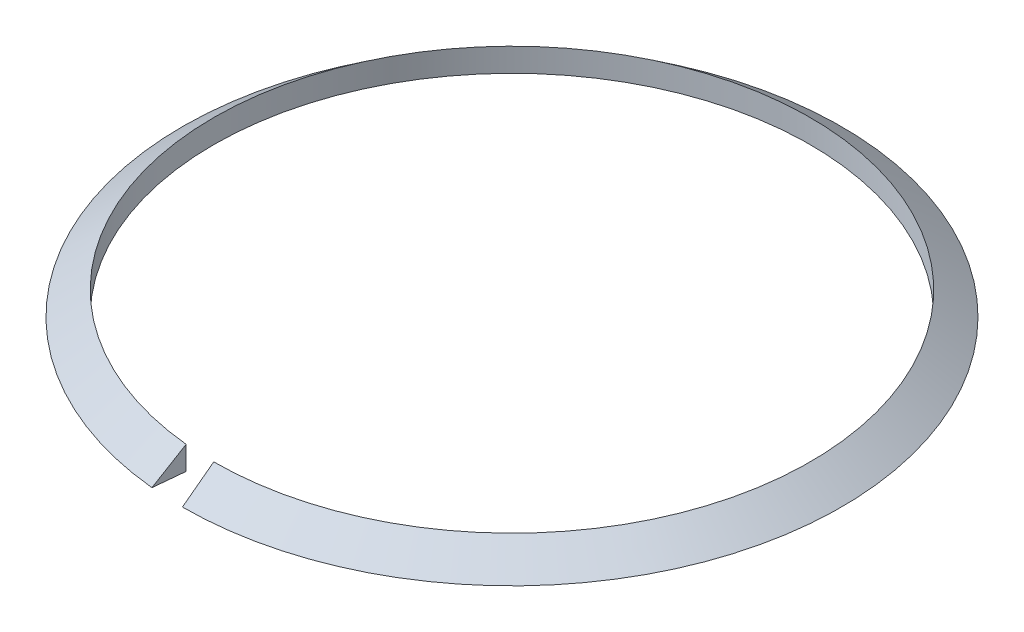
SolidWorks part; units mm, degrees
material "Cast Alloy Steel"
ref_plane "Front Plane" through (0, 0, 0) normal (0, 0, 1) x (1, 0, 0)
ref_plane "Top Plane" through (0, 0, 0) normal (0, 1, 0) x (1, 0, 0)
ref_plane "Right Plane" through (0, 0, 0) normal (1, 0, 0) x (0, 0, -1)
sketch "Sketch1" plane through (0, 0, 0) normal (1, 0, 0) x (0, 0, -1)
  line L0 (0, 0) -> (0, 10.6046) construction
  line L1 (0, 0) -> (-19.05, 0) construction
  line L2 (-19.05, 0.7506) -> (-19.05, -0.7506)
  line L3 (-19.05, -0.7506) -> (-21.049, -0.7506)
  line L4 (-21.049, -0.7506) -> (-19.05, 0.7506)
  dimension "D1" = 1.5011
  dimension "D2" = 1.999
  dimension "D3" = 38.1
revolve "Revolve1" add sketch "Sketch1" angle 354.415 about L0
